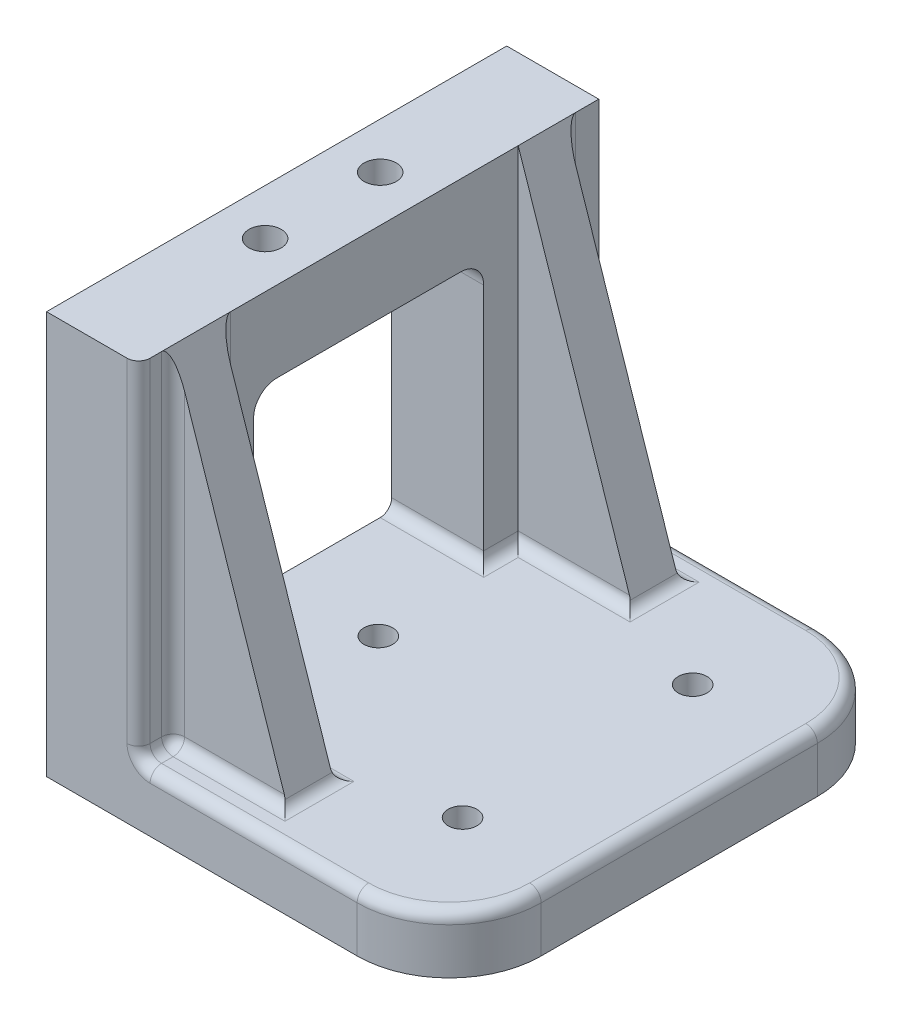
SolidWorks part; units mm, degrees
ref_plane "Front Plane" through (0, 0, 0) normal (0, 0, 1) x (1, 0, 0)
ref_plane "Top Plane" through (0, 0, 0) normal (0, 1, 0) x (1, 0, 0)
ref_plane "Right Plane" through (0, 0, 0) normal (1, 0, 0) x (0, 0, -1)
sketch "Sketch1" plane through (0, 0, 0) normal (0, 1, 0) x (1, 0, 0)
  line L0 (8.8397, 20) -> (26.1603, 30) construction
  line L1 (0, 0) -> (35, 0)
  line L2 (0, 0) -> (0, 40)
  line L3 (0, 40) -> (35, 40)
  line L4 (35, 0) -> (35, 40)
  line L5 (8.8397, 20) -> (26.1603, 10) construction
  line L6 (26.1603, 30) -> (26.1603, 10) construction
  line L7 (0, 20) -> (35, 20) construction
  line L8 (17.5, 40) -> (17.5, 0) construction
  circle A1 centre (26.1603, 30) radius 1.25
  circle A2 centre (8.8397, 20) radius 1.25
  circle A3 centre (26.1603, 10) radius 1.25
  point P12 (17.5, 25)
  dimension "D3" = 20
  dimension "D4" = 2.5
  dimension "D1" = 35
  dimension "D2" = 40
extrude "Boss-Extrude1" add sketch "Sketch1" along normal blind 5
fillet "Fillet1" radius 8 1 edges at (35, 2.5, 0)
fillet "Fillet2" radius 8 1 edges at (35, 2.5, -40)
sketch "Sketch2" plane through (0, 5, 0) normal (0, 1, 0) x (1, 0, 0)
  line L1 (0, 0) -> (8, 0)
  line L2 (0, 0) -> (0, 10)
  line L3 (0, 10) -> (8, 10)
  line L4 (8, 0) -> (8, 10)
  line L5 (0, 30) -> (8, 30)
  line L6 (0, 30) -> (0, 40)
  line L7 (0, 40) -> (8, 40)
  line L8 (8, 30) -> (8, 40)
  dimension "D1" = 8
  dimension "D2" = 20
extrude "Boss-Extrude2" add sketch "Sketch2" along normal blind 30
ref_plane "Plane1" through (0, 0, -5) normal (0, 0, 1) x (1, 0, 0)
sketch "Sketch4" plane through (0, 0, -5) normal (0, 0, 1) x (1, 0, 0)
  line L0 (8, 35) -> (18, 5)
  line L1 (27.4103, 5) -> (24.9103, 5) construction
  line L2 (8, 35) -> (8, 5) construction
  dimension "D1" = 10
rib "Rib1" sketch "Sketch4" sketch "Sketch4" thickness 4 extrusion direction parallel to sketch draft on no parameters "D1"=4
ref_plane "Plane2" through (0, 0, -20) normal (0, 0, -1) x (-1, 0, 0)
mirror "Mirror2" about plane through (0, 0, -20) normal (0, 0, -1) of "Rib1"
sketch "Sketch5" plane through (0, 0, -30) normal (0, 0, 1) x (1, 0, 0)
  line L0 (0, 5) -> (8, 5) construction
  line L1 (0, 35) -> (8, 35)
  line L2 (0, 35) -> (0, 28)
  line L3 (0, 28) -> (8, 28)
  line L4 (8, 35) -> (8, 28)
  dimension "D1" = 23
extrude "Boss-Extrude3" add sketch "Sketch5" along normal up to next
sketch "Sketch6" plane through (0, 35, 0) normal (0, 1, 0) x (1, 0, 0)
  line L1 (4, 0) -> (4, 40) construction
  line L2 (0, 0) -> (8, 0) construction
  line L3 (8, 40) -> (0, 40) construction
  circle A0 centre (4, 15) radius 1.4
  circle A1 centre (4, 25) radius 1.4
  dimension "D1" = 2.8
  dimension "D2" = 10
  dimension "D3" = 15
extrude "Cut-Extrude1" cut sketch "Sketch6" against normal up to next
fillet "Fillet7" radius 1 20 edges at (8, 20, 0) (32.6569, 5, -37.6569) (17.5, 5, -40) (8, 20, -37) (13, 5, -37) (18, 5, -35) (13, 5, -33) (8, 5, -31.5) (4, 5, -30) (4, 5, -10) (8, 5, -8.5) (35, 5, -20) (32.6569, 5, -2.3431) (8, 20, -3) (8, 20, -7) (13, 5, -7) (18, 5, -5) (13, 5, -3) (17.5, 5, 0) (8, 5, -1.5)
fillet "Fillet8" radius 2 2 edges at (4, 28, -30) (4, 28, -10)
